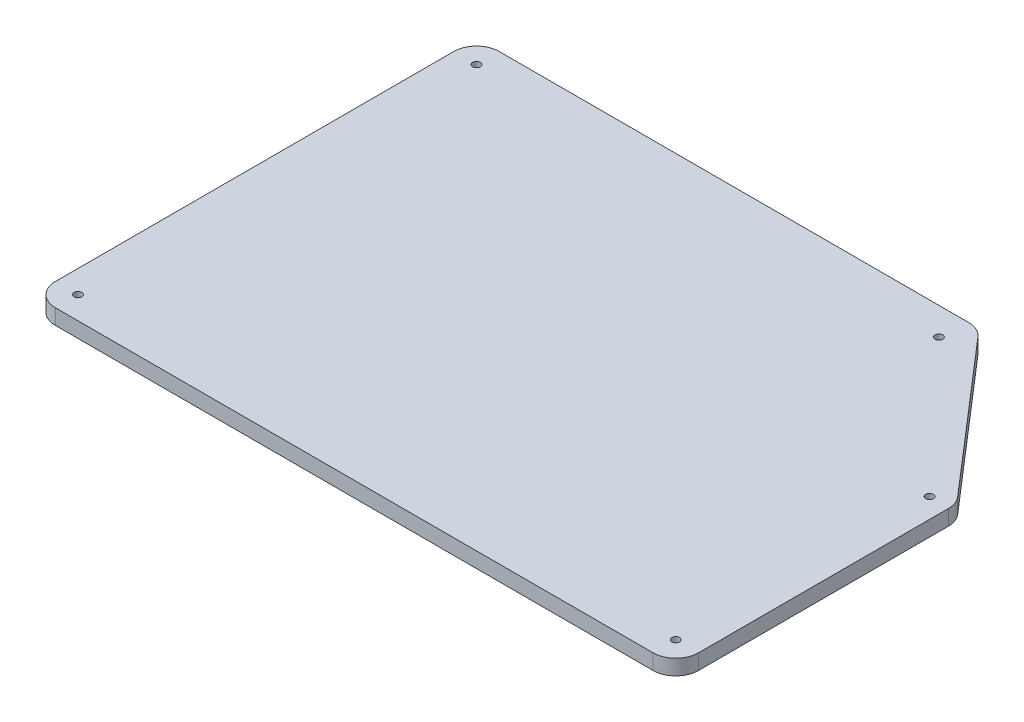
SolidWorks part; units mm, degrees
ref_plane "前视基准面" through (0, 0, 0) normal (0, 0, 1) x (1, 0, 0)
ref_plane "上视基准面" through (0, 0, 0) normal (0, 1, 0) x (1, 0, 0)
ref_plane "右视基准面" through (0, 0, 0) normal (1, 0, 0) x (0, 0, -1)
sketch "草图2" plane through (0, 0, 0) normal (0, 1, 0) x (1, 0, 0)
  line L0 (-119.1312, 58.0082) -> (34.0133, 58.0082)
  line L1 (-126.6312, 50.5082) -> (-126.6312, -79.4918)
  line L2 (-119.1312, -86.9918) -> (75.8688, -86.9918)
  line L3 (83.3688, 2.0316) -> (83.3688, -79.4918)
  line L4 (39.6901, 55.4097) -> (81.5456, 6.933)
  line L5 (70.2075, 41.487) -> (9.1579, -11.2242) construction
  line L6 (-119.1312, 57.9082) -> (34.0133, 57.9082)
  line L12 (39.6144, 55.3443) -> (81.4699, 6.8677)
  line L13 (83.2688, 2.0316) -> (83.2688, -79.4918)
  line L14 (-119.1312, -86.8918) -> (75.8688, -86.8918)
  line L15 (-126.5312, 50.5082) -> (-126.5312, -79.4918)
  line L16 (70.2729, 41.4113) -> (9.2233, -11.2998)
  line L17 (11.9793, -14.3918) -> (83.3688, -14.3918)
  line L37 (11.9793, -14.4918) -> (83.3688, -14.4918) construction
  arc A0 (-119.1312, 58.0082) -> (-126.6312, 50.5082) centre (-119.1312, 50.5082) ccw
  arc A1 (-126.6312, -79.4918) -> (-119.1312, -86.9918) centre (-119.1312, -79.4918) ccw
  arc A2 (75.8688, -86.9918) -> (83.3688, -79.4918) centre (75.8688, -79.4918) ccw
  arc A3 (39.6901, 55.4097) -> (34.0133, 58.0082) centre (34.0133, 50.5082) ccw
  arc A4 (83.3688, 2.0316) -> (81.5456, 6.933) centre (75.8688, 2.0316) ccw
  arc A10 (39.6144, 55.3443) -> (34.0133, 57.9082) centre (34.0133, 50.5082) ccw
  arc A11 (83.2688, 2.0316) -> (81.4699, 6.8677) centre (75.8688, 2.0316) ccw
  arc A12 (75.8688, -86.8918) -> (83.2688, -79.4918) centre (75.8688, -79.4918) ccw
  arc A13 (-126.5312, -79.4918) -> (-119.1312, -86.8918) centre (-119.1312, -79.4918) ccw
  arc A14 (-119.1312, 57.9082) -> (-126.5312, 50.5082) centre (-119.1312, 50.5082) ccw
  circle A15 centre (76.8106, 2.3819) radius 1.25
  circle A16 centre (33.2914, 48.9311) radius 1.25
  circle A17 centre (-119.1312, 50.5082) radius 1.25
  circle A18 centre (-119.1312, -79.4918) radius 1.25
  circle A19 centre (75.8688, -79.4918) radius 1.25
  point P30 (-126.6312, -14.4918)
  point P33 (5.3734, -14.4918)
  point P80 (0, 0)
  point P81 (0, 0)
  dimension "D1" = 0.1
extrude "凸台-拉伸1" add sketch "草图2" along normal blind 5
